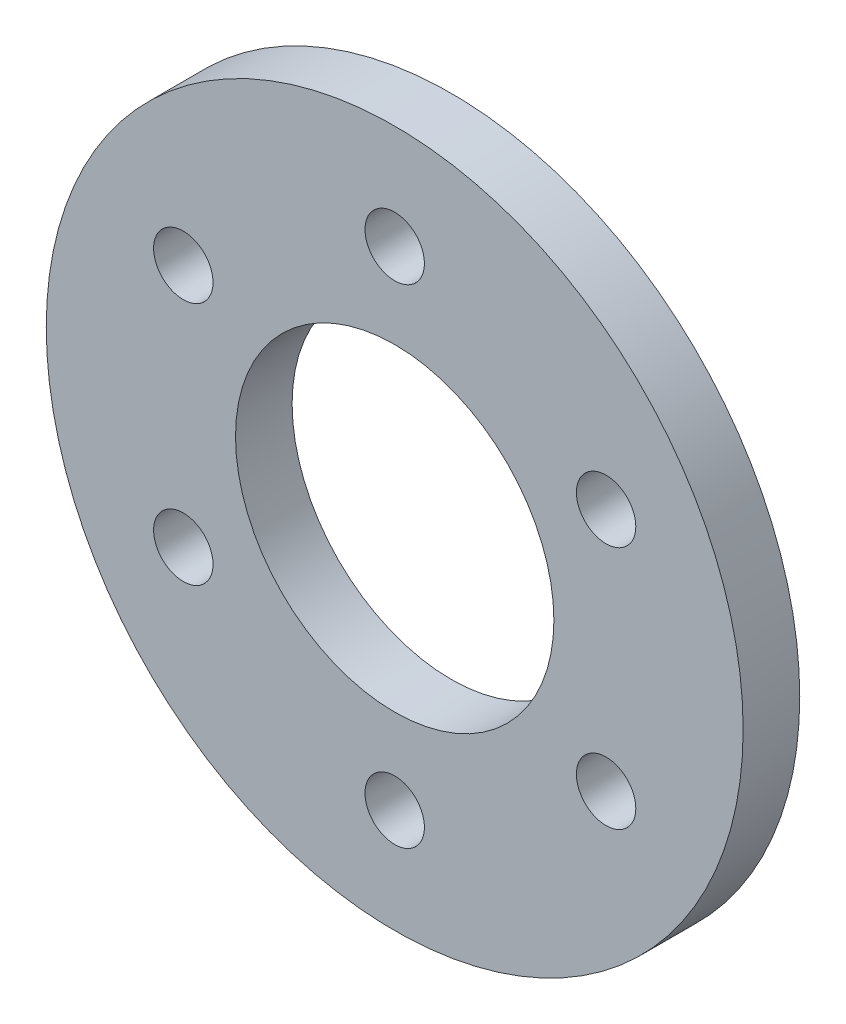
SolidWorks part; units mm, degrees
material "Thornel Mat VMA"
ref_plane "前视基准面" through (0, 0, 0) normal (0, 0, 1) x (1, 0, 0)
ref_plane "上视基准面" through (0, 0, 0) normal (0, 1, 0) x (1, 0, 0)
ref_plane "右视基准面" through (0, 0, 0) normal (1, 0, 0) x (0, 0, -1)
other "Configuration Table"
sketch "草图1" plane through (0, 0, 0) normal (0, 0, 1) x (1, 0, 0)
  line L0 (0, 17.25) -> (0, 30.625) construction
  line L1 (0, 30.625) -> (0, 44) construction
  line L2 (-19.6854, 23.4601) -> (0, 0) construction
  line L3 (0, 0) -> (19.6854, 23.4601) construction
  circle A0 centre (0, 0) radius 17.25 construction
  circle A1 centre (0, 0) radius 11.25
  circle A2 centre (0, 0) radius 44
  circle A3 centre (0, 17.25) radius 2.1
  circle A4 centre (14.9389, 8.625) radius 2.1
  circle A5 centre (14.9389, -8.625) radius 2.1
  circle A6 centre (0, -17.25) radius 2.1
  circle A7 centre (-14.9389, -8.625) radius 2.1
  circle A8 centre (-14.9389, 8.625) radius 2.1
  circle A9 centre (0, 0) radius 30.625 construction
  arc A10 (-19.6854, 23.4601) -> (19.6854, 23.4601) centre (0, 0) cw construction
  arc A11 (23.5421, 28.0564) -> (-23.5421, 28.0564) centre (0, 0) ccw
  arc A12 (15.8286, 18.8638) -> (-15.8286, 18.8638) centre (0, 0) ccw
  arc A13 (15.8286, 18.8638) -> (23.5421, 28.0564) centre (19.6854, 23.4601) ccw
  arc A14 (-23.5421, 28.0564) -> (-15.8286, 18.8638) centre (-19.6854, 23.4601) ccw
  arc A15 (30.1597, 5.318) -> (10.4744, -28.7781) centre (0, 0) cw construction
  arc A16 (12.5265, -34.4162) -> (36.0686, 6.3599) centre (0, 0) ccw
  arc A17 (8.4222, -23.1399) -> (24.2509, 4.2761) centre (0, 0) ccw
  arc A18 (8.4222, -23.1399) -> (12.5265, -34.4162) centre (10.4744, -28.7781) ccw
  arc A19 (36.0686, 6.3599) -> (24.2509, 4.2761) centre (30.1597, 5.318) ccw
  arc A20 (-10.4744, -28.7781) -> (-30.1597, 5.318) centre (0, 0) cw construction
  arc A21 (-36.0686, 6.3599) -> (-12.5265, -34.4162) centre (0, 0) ccw
  arc A22 (-24.2509, 4.2761) -> (-8.4222, -23.1399) centre (0, 0) ccw
  arc A23 (-24.2509, 4.2761) -> (-36.0686, 6.3599) centre (-30.1597, 5.318) ccw
  arc A24 (-12.5265, -34.4162) -> (-8.4222, -23.1399) centre (-10.4744, -28.7781) ccw
  point P20 (0, 0)
  point P24 (0, 30.625)
  point P36 (26.522, -15.3125)
  point P43 (-26.522, -15.3125)
  point P48 (0, 0)
  dimension "D1" = 34.5
  dimension "D2" = 6
  dimension "D3" = 88
  dimension "D4" = 4.2
  dimension "D6" = 6
  dimension "D7" = 40
  dimension "D5" = 6
  dimension "D8" = 3
extrude "凸台-拉伸1" add sketch "草图1" along normal blind 4
sketch "草图2" plane through (0, 0, 4) normal (0, 0, 1) x (1, 0, 0)
  circle A0 centre (0, 0) radius 24.625
  arc A1 (15.8286, 18.8638) -> (-15.8286, 18.8638) centre (0, 0) ccw construction
extrude "切除-拉伸1" cut sketch "草图2" against normal blind 10 flip side to cut
